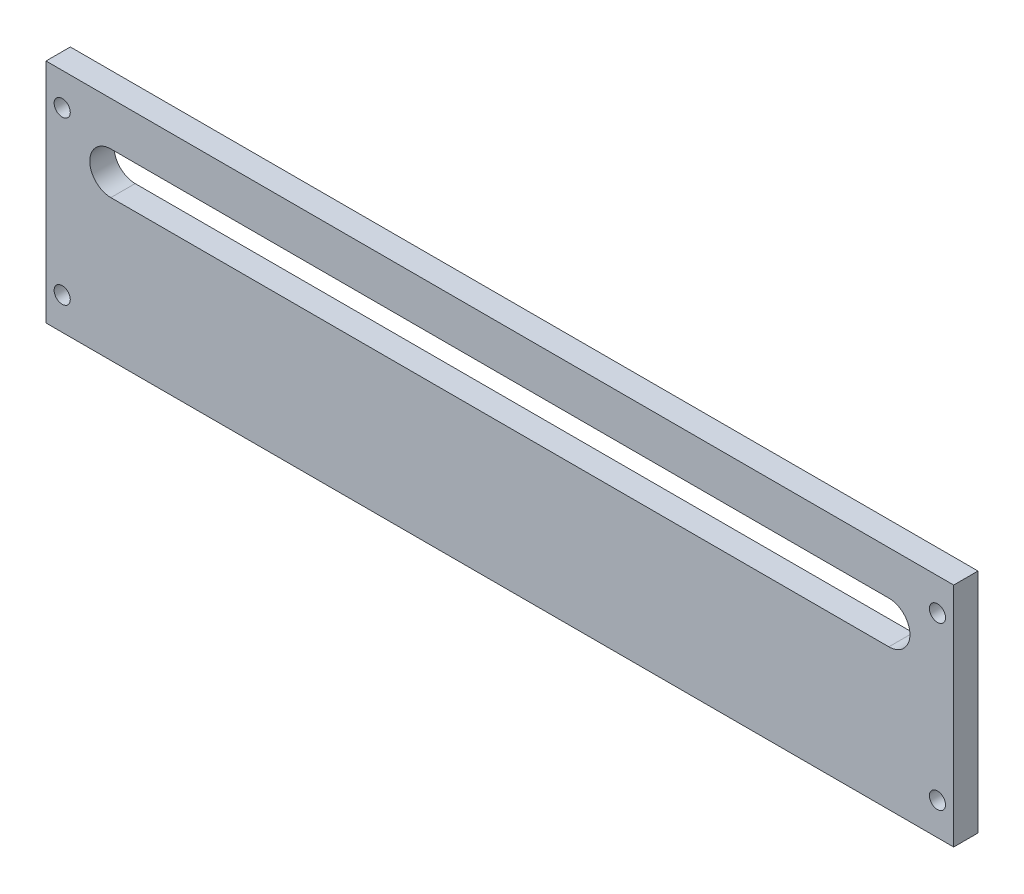
SolidWorks part; units mm, degrees
ref_plane "Front Plane" through (0, 0, 0) normal (0, 0, 1) x (1, 0, 0)
ref_plane "Top Plane" through (0, 0, 0) normal (0, 1, 0) x (1, 0, 0)
ref_plane "Right Plane" through (0, 0, 0) normal (1, 0, 0) x (0, 0, -1)
sketch "Sketch1" plane through (0, 0, 0) normal (0, 0, 1) x (1, 0, 0)
  line L1 (0, 0) -> (355.6, 0)
  line L2 (0, 0) -> (0, 88.9)
  line L3 (0, 88.9) -> (355.6, 88.9)
  line L4 (355.6, 0) -> (355.6, 88.9)
  dimension "D1" = 88.9
  dimension "D2" = 355.6
extrude "Boss-Extrude1" add sketch "Sketch1" along normal blind 9.525
sketch "Sketch2" plane through (0, 0, 9.525) normal (0, 0, 1) x (1, 0, 0)
  line L0 (0, 88.9) -> (0, 0) construction
  line L1 (355.6, 88.9) -> (0, 88.9) construction
  line L2 (0, 0) -> (355.6, 0) construction
  line L3 (355.6, 0) -> (355.6, 88.9) construction
  circle A0 centre (6.35, 76.2) radius 3.1623
  circle A1 centre (6.35, 12.7) radius 3.1623
  circle A2 centre (349.25, 76.2) radius 3.1623
  circle A3 centre (349.25, 12.7) radius 3.1623
  dimension "D1" = 6.3246
  dimension "D2" = 6.3246
  dimension "D3" = 6.3246
  dimension "D4" = 6.3246
  dimension "D5" = 6.35
  dimension "D6" = 12.7
  dimension "D7" = 6.35
  dimension "D8" = 12.7
  dimension "D9" = 12.7
  dimension "D10" = 12.7
  dimension "D11" = 6.35
  dimension "D12" = 6.35
extrude "Cut-Extrude1" cut sketch "Sketch2" against normal through all
sketch "Sketch3" plane through (0, 0, 9.525) normal (0, 0, 1) x (1, 0, 0)
  line L0 (25.4, 63.5) -> (330.2, 63.5) construction
  line L1 (25.4, 71.755) -> (330.2, 71.755)
  line L2 (25.4, 55.245) -> (330.2, 55.245)
  line L3 (0, 88.9) -> (0, 0) construction
  line L5 (355.6, 88.9) -> (0, 88.9) construction
  arc A0 (25.4, 71.755) -> (25.4, 55.245) centre (25.4, 63.5) ccw
  arc A1 (330.2, 55.245) -> (330.2, 71.755) centre (330.2, 63.5) ccw
  point P2 (177.8, 63.5)
  dimension "D1" = 8.255
  dimension "D2" = 304.8
  dimension "D3" = 25.4
  dimension "D4" = 25.4
extrude "Cut-Extrude2" cut sketch "Sketch3" against normal through all
